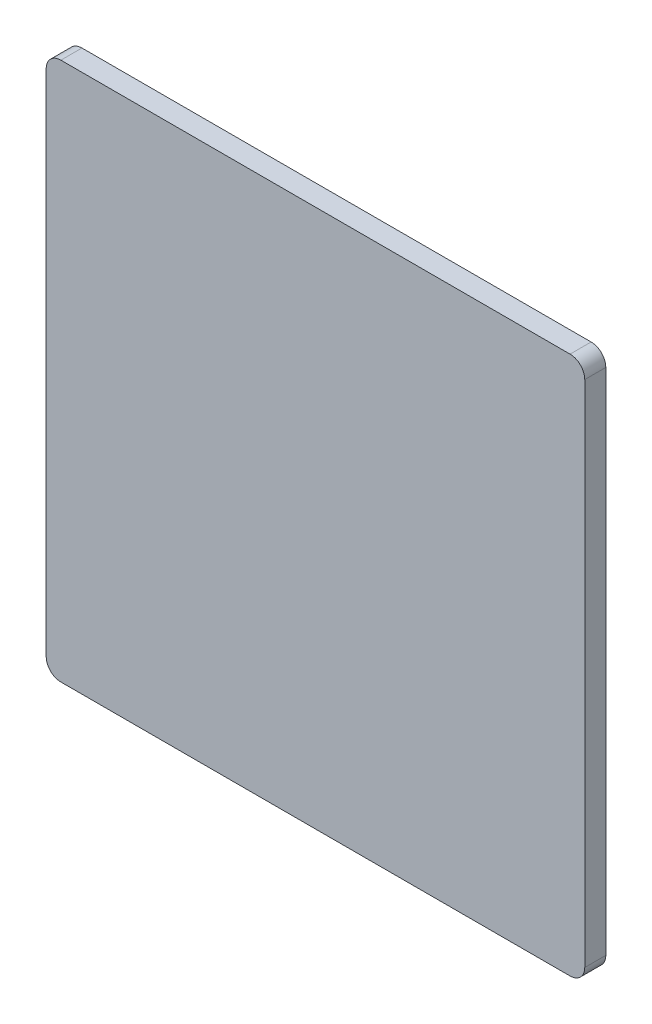
SolidWorks part; units mm, degrees
material "丙烯酸(中高冲击)"
ref_plane "前视基准面" through (0, 0, 0) normal (0, 0, 1) x (1, 0, 0)
ref_plane "上视基准面" through (0, 0, 0) normal (0, 1, 0) x (1, 0, 0)
ref_plane "右视基准面" through (0, 0, 0) normal (1, 0, 0) x (0, 0, -1)
sketch "草图1" plane through (0, 0, 0) normal (0, 0, 1) x (1, 0, 0)
  line L1 (-55, 55) -> (55, 55)
  line L2 (-55, 55) -> (-55, -55)
  line L3 (-55, -55) -> (55, -55)
  line L4 (55, 55) -> (55, -55)
  line L5 (-55, 55) -> (55, -55) construction
  line L6 (-55, -55) -> (55, 55) construction
  point P0 (0, 0)
  dimension "D1" = 110
  dimension "D2" = 110
extrude "凸台-拉伸1" add sketch "草图1" along normal blind 4.3
fillet "圆角1" radius 3 4 edges at (55, -55, 2.15) (-55, -55, 2.15) (55, 55, 2.15) (-55, 55, 2.15)
